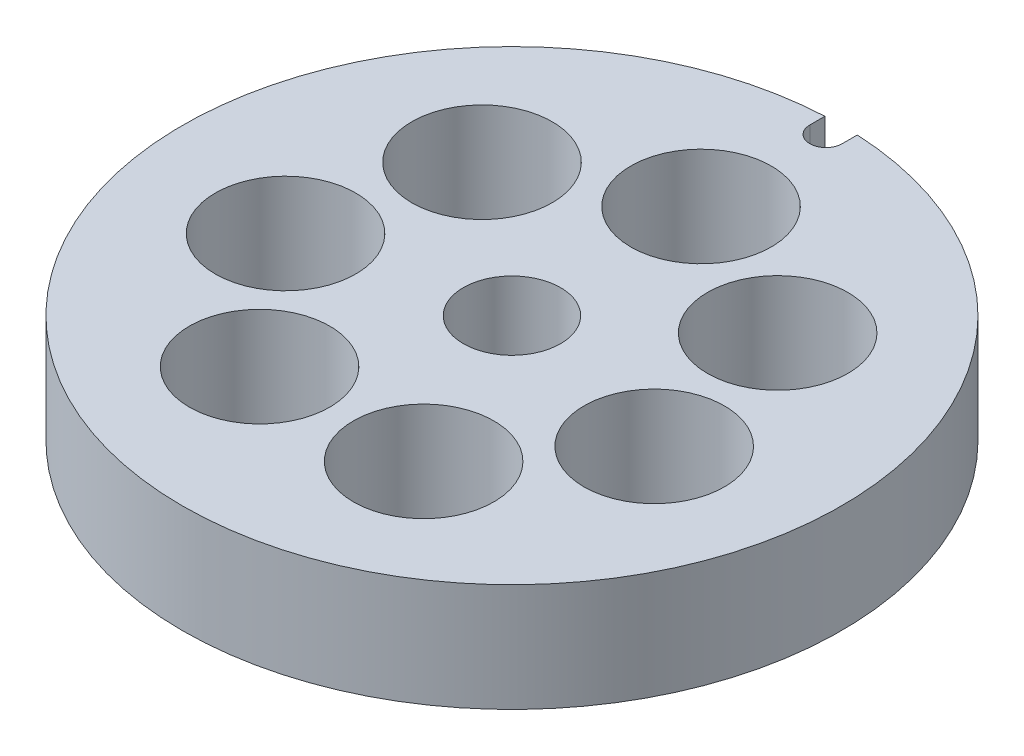
SolidWorks part; units mm, degrees
ref_plane "Płaszczyzna przednia" through (0, 0, 0) normal (0, 0, 1) x (1, 0, 0)
ref_plane "Płaszczyzna górna" through (0, 0, 0) normal (0, 1, 0) x (1, 0, 0)
ref_plane "Płaszczyzna prawa" through (0, 0, 0) normal (1, 0, 0) x (0, 0, -1)
sketch "Szkic1" plane through (0, 0, 0) normal (0, 1, 0) x (1, 0, 0)
  line L0 (-1.5, 30.4631) -> (-1.5, 29.0631)
  line L1 (1.5, 29.0631) -> (1.5, 30.4631)
  arc A0 (-1.5, 30.4631) -> (1.5, 30.4631) centre (0, 0) ccw
  circle A1 centre (0, 0) radius 4.5
  circle A2 centre (0, 17.5) radius 6.5
  circle A3 centre (13.6821, 10.9111) radius 6.5
  circle A4 centre (17.0612, -3.8941) radius 6.5
  circle A5 centre (7.593, -15.767) radius 6.5
  circle A6 centre (-7.593, -15.767) radius 6.5
  circle A7 centre (-17.0612, -3.8941) radius 6.5
  circle A8 centre (-13.6821, 10.9111) radius 6.5
  arc A9 (-1.5, 29.0631) -> (1.5, 29.0631) centre (0, 29.0631) ccw
  point P8 (-0.653, 28.0971)
  point P21 (0, 0)
  point P25 (0, 0)
  point P26 (0, 28.0823)
  dimension "D1" = 9
  dimension "D2" = 61
  dimension "D4" = 13
  dimension "D6" = 1.5
  dimension "D3" = 17.5
  dimension "D8" = 1.4
  dimension "D5" = 7
extrude "Dodanie-wyciągnięcie1" add sketch "Szkic1" along normal blind 10
